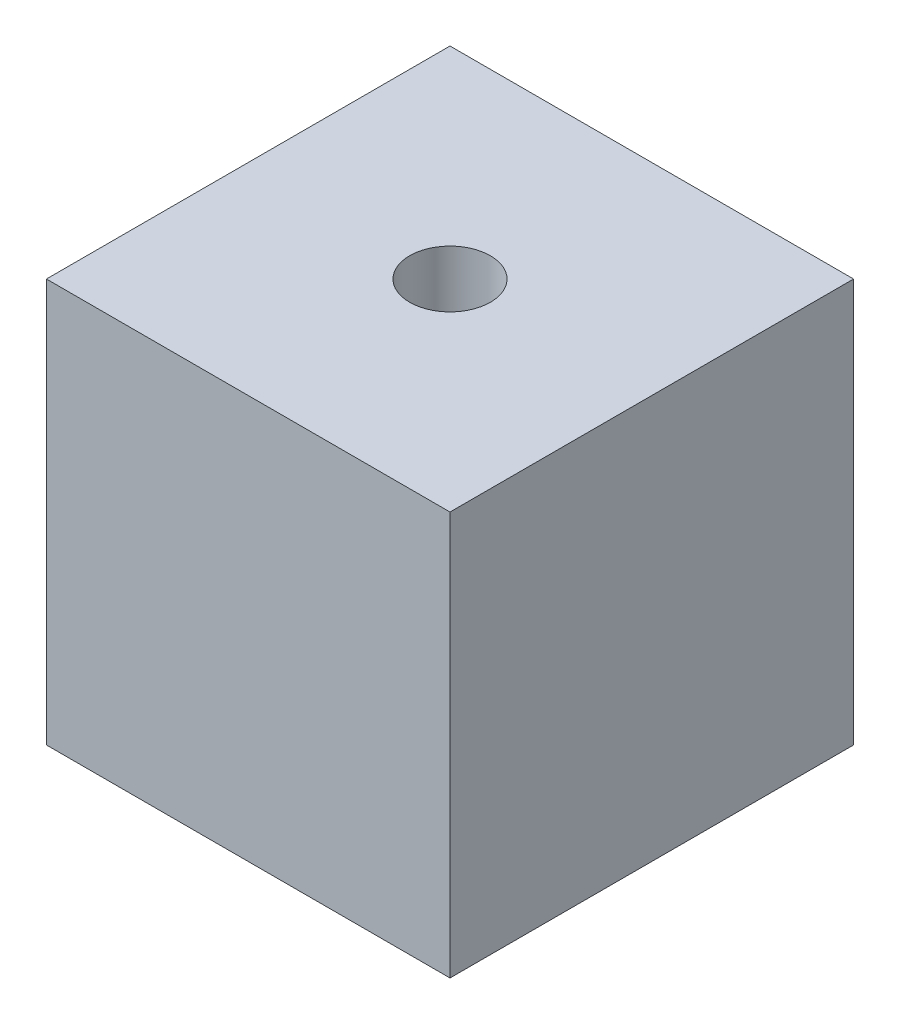
SolidWorks part; units mm, degrees
ref_plane "Plan de face" through (0, 0, 0) normal (0, 0, 1) x (1, 0, 0)
ref_plane "Plan de dessus" through (0, 0, 0) normal (0, 1, 0) x (1, 0, 0)
ref_plane "Plan de droite" through (0, 0, 0) normal (1, 0, 0) x (0, 0, -1)
sketch "Sketch1" plane through (0, 0, 0) normal (0, 1, 0) x (1, 0, 0)
  line L1 (7.5, -7.5) -> (-7.5, -7.5)
  line L2 (7.5, -7.5) -> (7.5, 7.5)
  line L3 (7.5, 7.5) -> (-7.5, 7.5)
  line L4 (-7.5, -7.5) -> (-7.5, 7.5)
  line L5 (7.5, -7.5) -> (-7.5, 7.5) construction
  line L6 (7.5, 7.5) -> (-7.5, -7.5) construction
  point P0 (0, 0)
  dimension "D1" = 15
  dimension "D2" = 15
extrude "Boss-Extrude1" add sketch "Sketch1" along normal blind 15
sketch "Sketch2" plane through (0, 15, 0) normal (0, 1, 0) x (-1, 0, 0)
  circle A0 centre (0, 0) radius 1.5
extrude "Cut-Extrude1" cut sketch "Sketch2" against normal through all
